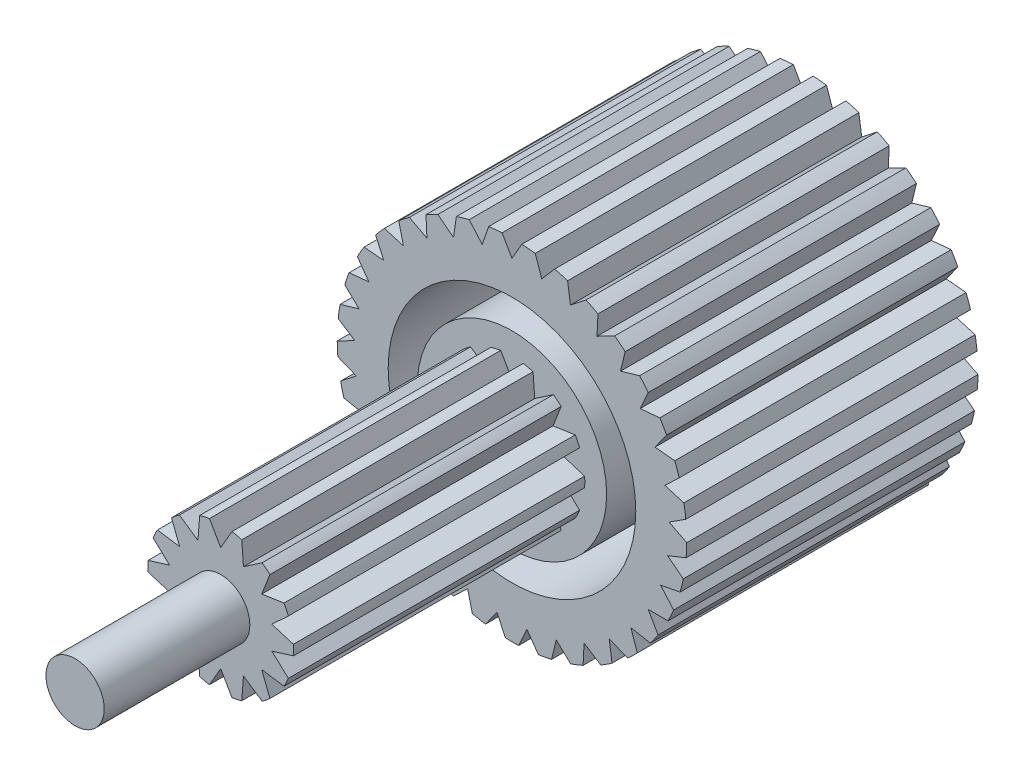
SolidWorks part; units mm, degrees
ref_plane "Front Plane" through (0, 0, 0) normal (0, 0, 1) x (1, 0, 0)
ref_plane "Top Plane" through (0, 0, 0) normal (0, 1, 0) x (1, 0, 0)
ref_plane "Right Plane" through (0, 0, 0) normal (1, 0, 0) x (0, 0, -1)
sketch "Sketch1" plane through (0, 0, 0) normal (0, 0, 1) x (1, 0, 0)
  circle A0 centre (0, 0) radius 15.24
  dimension "D1" = 30.48
extrude "Boss-Extrude1" add sketch "Sketch1" along normal blind 25.4
sketch "Sketch2" plane through (0, 0, 25.4) normal (0, 0, 1) x (1, 0, 0)
  line L0 (2.5958, 13.4681) -> (4.3244, 15.463)
  line L1 (0, 13.716) -> (1.3198, 16.002)
  line L2 (1.3198, 16.002) -> (-1.3198, 16.002)
  line L3 (-1.3198, 16.002) -> (0, 13.716)
  line L4 (4.3244, 15.463) -> (1.7324, 15.9626)
  line L5 (1.7324, 15.9626) -> (2.5958, 13.4681)
  line L6 (5.0977, 12.7335) -> (7.1726, 14.3652)
  line L7 (7.1726, 14.3652) -> (4.7221, 15.3463)
  line L8 (4.7221, 15.3463) -> (5.0977, 12.7335)
  line L9 (7.4154, 11.5386) -> (9.7616, 12.7482)
  line L10 (9.7616, 12.7482) -> (7.541, 14.1753)
  line L11 (7.541, 14.1753) -> (7.4154, 11.5386)
  line L12 (9.4651, 9.9267) -> (11.9978, 10.6704)
  line L13 (11.9978, 10.6704) -> (10.0874, 12.492)
  line L14 (10.0874, 12.492) -> (9.4651, 9.9267)
  line L15 (11.1727, 7.9561) -> (13.8004, 8.207)
  line L16 (13.8004, 8.207) -> (12.2693, 10.3572)
  line L17 (12.2693, 10.3572) -> (11.1727, 7.9561)
  line L18 (12.4765, 5.6978) -> (15.1042, 5.4469)
  line L19 (15.1042, 5.4469) -> (14.0077, 7.848)
  line L20 (14.0077, 7.848) -> (12.4765, 5.6978)
  line L21 (13.3294, 3.2337) -> (15.8621, 2.49)
  line L22 (15.8621, 2.49) -> (15.2398, 5.0552)
  line L23 (15.2398, 5.0552) -> (13.3294, 3.2337)
  line L24 (13.7005, 0.6526) -> (16.0467, -0.5569)
  line L25 (16.0467, -0.5569) -> (15.9211, 2.0797)
  line L26 (15.9211, 2.0797) -> (13.7005, 0.6526)
  line L27 (13.5764, -1.952) -> (15.6513, -3.5837)
  line L28 (15.6513, -3.5837) -> (16.027, -0.9709)
  line L29 (16.027, -0.9709) -> (13.5764, -1.952)
  line L30 (12.9616, -4.4861) -> (14.6902, -6.481)
  line L31 (14.6902, -6.481) -> (15.5536, -3.9865)
  line L32 (15.5536, -3.9865) -> (12.9616, -4.4861)
  line L33 (11.8784, -6.858) -> (13.1982, -9.144)
  line L34 (13.1982, -9.144) -> (14.518, -6.858)
  line L35 (14.518, -6.858) -> (11.8784, -6.858)
  line L36 (10.3659, -8.9821) -> (11.2292, -11.4765)
  line L37 (11.2292, -11.4765) -> (12.9578, -9.4816)
  line L38 (12.9578, -9.4816) -> (10.3659, -8.9821)
  line L39 (8.4787, -10.7815) -> (8.8543, -13.3943)
  line L40 (8.8543, -13.3943) -> (10.9292, -11.7626)
  line L41 (10.9292, -11.7626) -> (8.4787, -10.7815)
  line L42 (6.285, -12.1913) -> (6.1594, -14.8279)
  line L43 (6.1594, -14.8279) -> (8.5056, -13.6184)
  line L44 (8.5056, -13.6184) -> (6.285, -12.1913)
  line L45 (3.8642, -13.1604) -> (3.2419, -15.7256)
  line L46 (3.2419, -15.7256) -> (5.7746, -14.982)
  line L47 (5.7746, -14.982) -> (3.8642, -13.1604)
  line L48 (1.3038, -13.6539) -> (0.2072, -16.055)
  line L49 (0.2072, -16.055) -> (2.8349, -15.8041)
  line L50 (2.8349, -15.8041) -> (1.3038, -13.6539)
  line L51 (-1.3038, -13.6539) -> (-2.8349, -15.8041)
  line L52 (-2.8349, -15.8041) -> (-0.2072, -16.055)
  line L53 (-0.2072, -16.055) -> (-1.3038, -13.6539)
  line L54 (-3.8642, -13.1604) -> (-5.7746, -14.982)
  line L55 (-5.7746, -14.982) -> (-3.2419, -15.7256)
  line L56 (-3.2419, -15.7256) -> (-3.8642, -13.1604)
  line L57 (-6.285, -12.1913) -> (-8.5056, -13.6184)
  line L58 (-8.5056, -13.6184) -> (-6.1594, -14.8279)
  line L59 (-6.1594, -14.8279) -> (-6.285, -12.1913)
  line L60 (-8.4787, -10.7815) -> (-10.9292, -11.7626)
  line L61 (-10.9292, -11.7626) -> (-8.8543, -13.3943)
  line L62 (-8.8543, -13.3943) -> (-8.4787, -10.7815)
  line L63 (-10.3659, -8.9821) -> (-12.9578, -9.4816)
  line L64 (-12.9578, -9.4816) -> (-11.2292, -11.4765)
  line L65 (-11.2292, -11.4765) -> (-10.3659, -8.9821)
  line L66 (-11.8784, -6.858) -> (-14.518, -6.858)
  line L67 (-14.518, -6.858) -> (-13.1982, -9.144)
  line L68 (-13.1982, -9.144) -> (-11.8784, -6.858)
  line L69 (-12.9616, -4.4861) -> (-15.5536, -3.9865)
  line L70 (-15.5536, -3.9865) -> (-14.6902, -6.481)
  line L71 (-14.6902, -6.481) -> (-12.9616, -4.4861)
  line L72 (-13.5764, -1.952) -> (-16.027, -0.9709)
  line L73 (-16.027, -0.9709) -> (-15.6513, -3.5837)
  line L74 (-15.6513, -3.5837) -> (-13.5764, -1.952)
  line L75 (-13.7005, 0.6526) -> (-15.9211, 2.0797)
  line L76 (-15.9211, 2.0797) -> (-16.0467, -0.5569)
  line L77 (-16.0467, -0.5569) -> (-13.7005, 0.6526)
  line L78 (-13.3294, 3.2337) -> (-15.2398, 5.0552)
  line L79 (-15.2398, 5.0552) -> (-15.8621, 2.49)
  line L80 (-15.8621, 2.49) -> (-13.3294, 3.2337)
  line L81 (-12.4765, 5.6978) -> (-14.0077, 7.848)
  line L82 (-14.0077, 7.848) -> (-15.1042, 5.4469)
  line L83 (-15.1042, 5.4469) -> (-12.4765, 5.6978)
  line L84 (-11.1727, 7.9561) -> (-12.2693, 10.3572)
  line L85 (-12.2693, 10.3572) -> (-13.8004, 8.207)
  line L86 (-13.8004, 8.207) -> (-11.1727, 7.9561)
  line L87 (-9.4651, 9.9267) -> (-10.0874, 12.492)
  line L88 (-10.0874, 12.492) -> (-11.9978, 10.6704)
  line L89 (-11.9978, 10.6704) -> (-9.4651, 9.9267)
  line L90 (-7.4154, 11.5386) -> (-7.541, 14.1753)
  line L91 (-7.541, 14.1753) -> (-9.7616, 12.7482)
  line L92 (-9.7616, 12.7482) -> (-7.4154, 11.5386)
  line L93 (-5.0977, 12.7335) -> (-4.7221, 15.3463)
  line L94 (-4.7221, 15.3463) -> (-7.1726, 14.3652)
  line L95 (-7.1726, 14.3652) -> (-5.0977, 12.7335)
  line L96 (-2.5958, 13.4681) -> (-1.7324, 15.9626)
  line L97 (-1.7324, 15.9626) -> (-4.3244, 15.463)
  line L98 (-4.3244, 15.463) -> (-2.5958, 13.4681)
  circle A0 centre (0, 15.24) radius 0.762 construction
  circle A1 centre (0, 0) radius 15.24 construction
  point P106 (0, 0)
  dimension "D1" = 1.524
  dimension "D2" = 33
extrude "Cut-Extrude1" cut sketch "Sketch2" against normal blind 25.4
sketch "Sketch3" plane through (0, 0, 25.4) normal (0, 0, 1) x (1, 0, 0)
  circle A0 centre (0, 0) radius 6.35
  dimension "D1" = 12.7
extrude "Boss-Extrude2" add sketch "Sketch3" along normal blind 25.4
sketch "Sketch5" plane through (0, 0, 50.8) normal (0, 0, 1) x (1, 0, 0)
  line L0 (1.9837, 4.1192) -> (4.5282, 5.854)
  line L1 (0, 4.572) -> (1.5398, 7.239)
  line L2 (1.5398, 7.239) -> (-1.5398, 7.239)
  line L3 (-1.5398, 7.239) -> (0, 4.572)
  line L4 (4.5282, 5.854) -> (1.7536, 7.1902)
  line L5 (1.7536, 7.1902) -> (1.9837, 4.1192)
  line L6 (3.5745, 2.8506) -> (6.6197, 3.3096)
  line L7 (6.6197, 3.3096) -> (4.6996, 5.7173)
  line L8 (4.6996, 5.7173) -> (3.5745, 2.8506)
  line L9 (4.4574, 1.0174) -> (7.4001, 0.1096)
  line L10 (7.4001, 0.1096) -> (6.7149, 3.112)
  line L11 (6.7149, 3.112) -> (4.4574, 1.0174)
  line L12 (4.4574, -1.0174) -> (6.7149, -3.112)
  line L13 (6.7149, -3.112) -> (7.4001, -0.1096)
  line L14 (7.4001, -0.1096) -> (4.4574, -1.0174)
  line L15 (3.5745, -2.8506) -> (4.6996, -5.7173)
  line L16 (4.6996, -5.7173) -> (6.6197, -3.3096)
  line L17 (6.6197, -3.3096) -> (3.5745, -2.8506)
  line L18 (1.9837, -4.1192) -> (1.7536, -7.1902)
  line L19 (1.7536, -7.1902) -> (4.5282, -5.854)
  line L20 (4.5282, -5.854) -> (1.9837, -4.1192)
  line L21 (0, -4.572) -> (-1.5398, -7.239)
  line L22 (-1.5398, -7.239) -> (1.5398, -7.239)
  line L23 (1.5398, -7.239) -> (0, -4.572)
  line L24 (-1.9837, -4.1192) -> (-4.5282, -5.854)
  line L25 (-4.5282, -5.854) -> (-1.7536, -7.1902)
  line L26 (-1.7536, -7.1902) -> (-1.9837, -4.1192)
  line L27 (-3.5745, -2.8506) -> (-6.6197, -3.3096)
  line L28 (-6.6197, -3.3096) -> (-4.6996, -5.7173)
  line L29 (-4.6996, -5.7173) -> (-3.5745, -2.8506)
  line L30 (-4.4574, -1.0174) -> (-7.4001, -0.1096)
  line L31 (-7.4001, -0.1096) -> (-6.7149, -3.112)
  line L32 (-6.7149, -3.112) -> (-4.4574, -1.0174)
  line L33 (-4.4574, 1.0174) -> (-6.7149, 3.112)
  line L34 (-6.7149, 3.112) -> (-7.4001, 0.1096)
  line L35 (-7.4001, 0.1096) -> (-4.4574, 1.0174)
  line L36 (-3.5745, 2.8506) -> (-4.6996, 5.7173)
  line L37 (-4.6996, 5.7173) -> (-6.6197, 3.3096)
  line L38 (-6.6197, 3.3096) -> (-3.5745, 2.8506)
  line L39 (-1.9837, 4.1192) -> (-1.7536, 7.1902)
  line L40 (-1.7536, 7.1902) -> (-4.5282, 5.854)
  line L41 (-4.5282, 5.854) -> (-1.9837, 4.1192)
  circle A0 centre (0, 6.35) radius 0.889 construction
  circle A1 centre (0, 0) radius 6.35 construction
  circle A2 centre (0, 0) radius 6.35 construction
  point P51 (0, 0)
  dimension "D1" = 1.778
  dimension "D2" = 14
extrude "Cut-Extrude2" cut sketch "Sketch5" against normal blind 25.4
sketch "Sketch6" plane through (0, 0, 25.4) normal (0, 0, 1) x (1, 0, 0)
  circle A0 centre (0, 0) radius 8.255
  circle A1 centre (0, 0) radius 10.795
  dimension "D1" = 16.51
  dimension "D2" = 21.59
extrude "Cut-Extrude3" cut sketch "Sketch6" against normal blind 10.16
sketch "Sketch7" plane through (0, 0, 0) normal (0, 0, -1) x (-1, 0, 0)
  circle A0 centre (0, 0) radius 10.795
  circle A1 centre (0, 0) radius 8.255
  dimension "D1" = 21.59
  dimension "D2" = 16.51
extrude "Cut-Extrude4" cut sketch "Sketch7" against normal blind 10.16
sketch "Sketch8" plane through (0, 0, 50.8) normal (0, 0, 1) x (1, 0, 0)
  circle A0 centre (0, 0) radius 2.54
  dimension "D1" = 5.08
extrude "Boss-Extrude3" add sketch "Sketch8" along normal blind 12.7
sketch "Sketch9" plane through (0, 0, 0) normal (0, 0, -1) x (-1, 0, 0)
  circle A0 centre (0, 0) radius 2.54
  dimension "D1" = 5.08
extrude "Boss-Extrude4" add sketch "Sketch9" along normal blind 3.81
